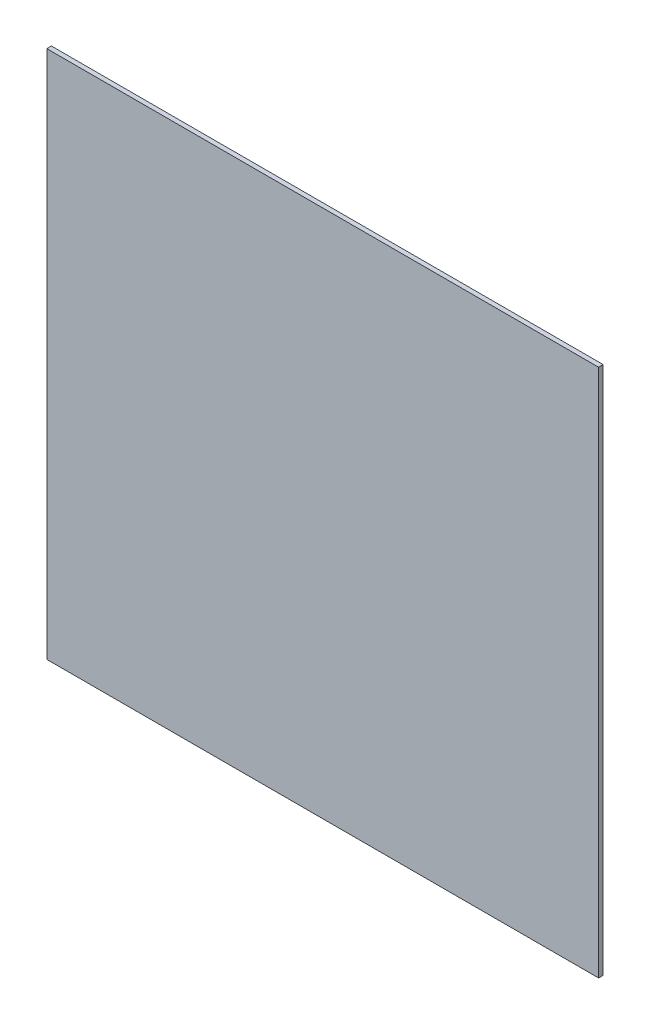
SolidWorks part; units mm, degrees
ref_plane "Plan de face" through (0, 0, 0) normal (0, 0, 1) x (1, 0, 0)
ref_plane "Plan de dessus" through (0, 0, 0) normal (0, 1, 0) x (1, 0, 0)
ref_plane "Plan de droite" through (0, 0, 0) normal (1, 0, 0) x (0, 0, -1)
sketch "Esquisse1" plane through (0, 0, 0) normal (0, 0, 1) x (1, 0, 0)
  line L1 (-302.5, 290) -> (302.5, 290)
  line L2 (-302.5, 290) -> (-302.5, -290)
  line L3 (-302.5, -290) -> (302.5, -290)
  line L4 (302.5, 290) -> (302.5, -290)
  line L5 (-302.5, 290) -> (302.5, -290) construction
  line L6 (-302.5, -290) -> (302.5, 290) construction
  point P0 (0, 0)
  dimension "D1" = 605
  dimension "D2" = 580
extrude "Boss.-Extru.1" add sketch "Esquisse1" along normal blind 5
